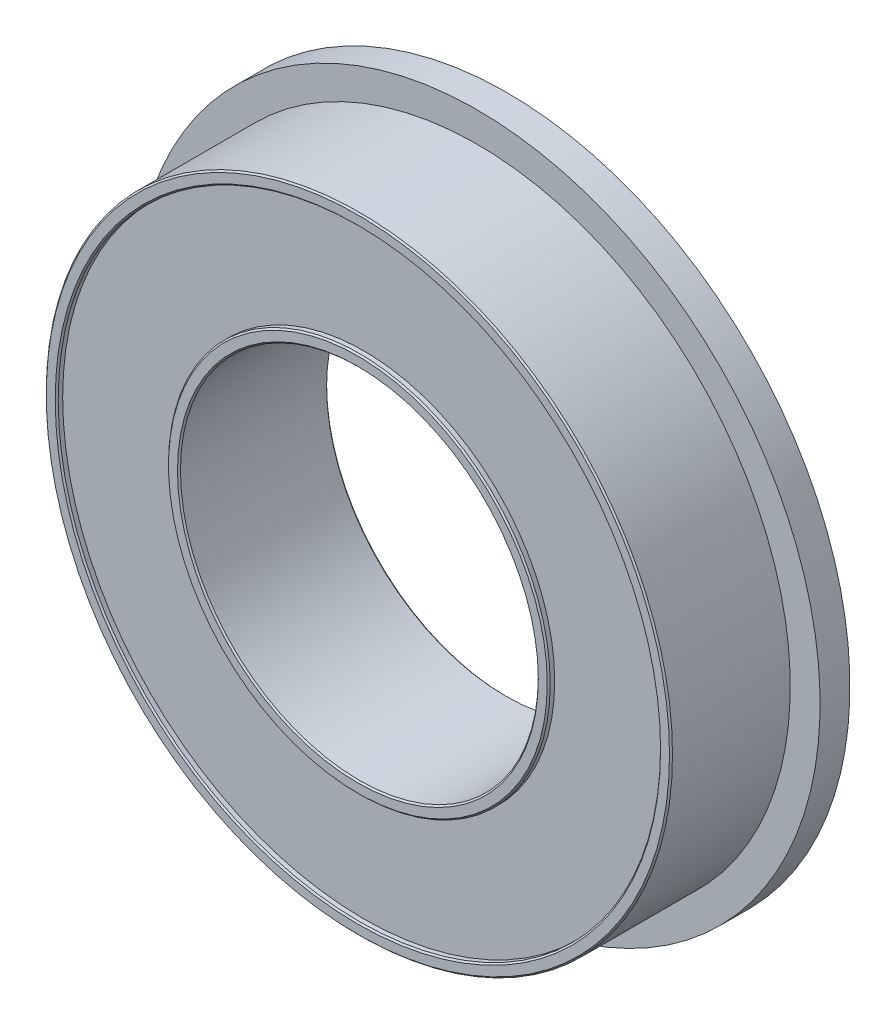
SolidWorks part; units mm, degrees
material "普通碳钢"
ref_plane "前视基准面" through (0, 0, 0) normal (0, 0, 1) x (1, 0, 0)
ref_plane "上视基准面" through (0, 0, 0) normal (0, 1, 0) x (1, 0, 0)
ref_plane "右视基准面" through (0, 0, 0) normal (1, 0, 0) x (0, 0, -1)
sketch "草图1" plane through (0, 0, 0) normal (0, 0, 1) x (1, 0, 0)
  circle A0 centre (0, 0) radius 6
  circle A1 centre (0, 0) radius 10.5
  dimension "D1" = 12
  dimension "D2" = 21
extrude "凸台-拉伸1" add sketch "草图1" along normal mid plane 5
sketch "草图3" plane through (0, 0, -2.5) normal (0, 0, -1) x (-1, 0, 0)
  circle A0 centre (0, 0) radius 6 construction
  circle A1 centre (0, 0) radius 6
  circle A2 centre (0, 0) radius 11.5
  dimension "D1" = 23
extrude "凸台-拉伸2" add sketch "草图3" against normal blind 1
sketch "草图4" plane through (0, 0, 2.5) normal (0, 0, 1) x (1, 0, 0)
  circle A2 centre (0, 0) radius 6.4
  circle A3 centre (0, 0) radius 6.4
  circle A6 centre (0, 0) radius 10.1
  circle A7 centre (0, 0) radius 10.1
  dimension "D1" = 0.4
  dimension "D2" = 0.4
extrude "切除-拉伸1" cut sketch "草图4" against normal blind 0.2
mirror "镜向1" about plane through (0, 0, 0) normal (0, 0, 1) of "切除-拉伸1"
chamfer "倒角1" distance 0.05 angle 45 7 edges at (6, 0, -2.5) (6.4, 0, -2.5) (6.4, 0, 2.5) (6, 0, 2.5) (10.5, 0, 2.5) (10.1, 0, 2.5) (10.1, 0, -2.5)
move or copy body "实体-移动/复制3" [suppressed] bodies to move or copy 109
move or copy body "实体-移动/复制1" [suppressed] bodies to move or copy 109
move or copy body "实体-移动/复制2" [suppressed] bodies to move or copy 109
equation "\"内径\"= 2"
equation "\"外径\"= 5"
equation "\"法兰外径\"= 6.1"
equation "\"宽度\"= 2.3"
equation "\"法兰宽度\"= 0.6"
equation "\"D1@草图1\"=\"内径\""
equation "\"D2@草图1\"=\"外径\""
equation "\"D1@草图3\"=\"法兰外径\""
equation "\"D1@凸台-拉伸1\"=\"宽度\""
equation "\"D1@凸台-拉伸2\"=\"法兰宽度\""
